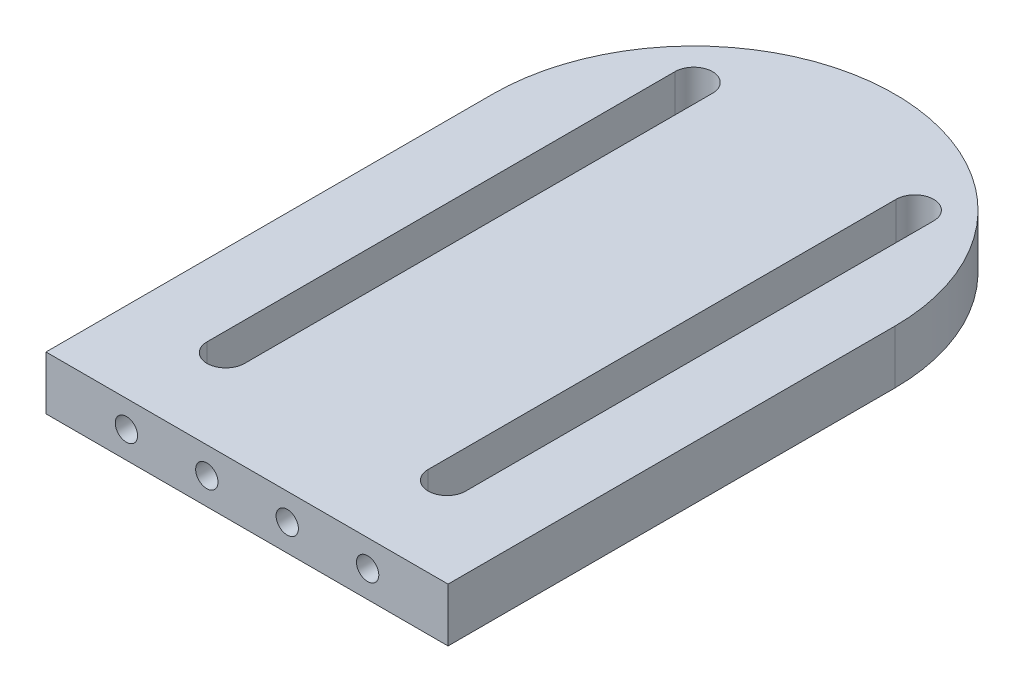
SolidWorks part; units mm, degrees
material "Сплав 2024"
ref_plane "Спереди" through (0, 0, 0) normal (0, 0, 1) x (1, 0, 0)
ref_plane "Сверху" through (0, 0, 0) normal (0, 1, 0) x (1, 0, 0)
ref_plane "Справа" through (0, 0, 0) normal (1, 0, 0) x (0, 0, -1)
sketch "Эскиз1" plane through (0, 0, 0) normal (0, 1, 0) x (1, 0, 0)
  line L2 (-15.9099, 15.9099) -> (15.9099, -15.9099) construction
  line L3 (15.9099, 15.9099) -> (-15.9099, -15.9099) construction
  line L4 (-22.5, 0) -> (-22.5, -50)
  line L5 (-22.5, -50) -> (22.5, -50)
  line L6 (22.5, 0) -> (22.5, -50)
  arc A0 (22.5, 0) -> (-22.5, 0) centre (0, 0) ccw
  dimension "D1" = 45
  dimension "D2" = 50
  dimension "D3" = 45
extrude "Бобышка-Вытянуть1" add sketch "Эскиз1" along normal blind 6
sketch "Эскиз2" plane through (0, 6, 0) normal (0, 1, 0) x (1, 0, 0)
  line L0 (-12.3744, -12.3744) -> (12.3744, 12.3744) construction
  line L1 (-36.6046, 36.6046) -> (36.6046, -36.6046) construction
  line L2 (22.5, -50) -> (22.5, 0) construction
  line L3 (-12.3744, 28.2466) -> (-12.3744, -50.5484) construction
  line L4 (12.3744, 23.4168) -> (12.3744, -56.6851) construction
  line L5 (-12.3744, 12.3744) -> (-12.3744, -40) construction
  line L6 (-10.2744, 12.3744) -> (-10.2744, -40)
  line L7 (-14.4744, 12.3744) -> (-14.4744, -40)
  line L8 (-22.5, -50) -> (22.5, -50) construction
  line L9 (0, 10.4779) -> (0, -10.8682) construction
  line L10 (12.3744, 12.3744) -> (12.3744, -40) construction
  line L11 (10.2744, 12.3744) -> (10.2744, -40)
  line L12 (14.4744, 12.3744) -> (14.4744, -40)
  circle A0 centre (0, 0) radius 6 construction
  circle A1 centre (0, 0) radius 17.5 construction
  arc A2 (-10.2744, 12.3744) -> (-14.4744, 12.3744) centre (-12.3744, 12.3744) ccw
  arc A3 (-14.4744, -40) -> (-10.2744, -40) centre (-12.3744, -40) ccw
  arc A4 (10.2744, 12.3744) -> (14.4744, 12.3744) centre (12.3744, 12.3744) cw
  arc A5 (14.4744, -40) -> (10.2744, -40) centre (12.3744, -40) cw
  point P12 (-12.3744, 12.3744)
  point P13 (12.3744, 12.3744)
  point P18 (-12.3744, -13.8128)
  point P28 (12.3744, -13.8128)
  dimension "D1" = 12
  dimension "D2" = 35
  dimension "D4" = 2.1
  dimension "D3" = 45
  dimension "D5" = 10
hole_wizard "Цековка для  винта с полукруглой головкой M31" [suppressed] positions "Эскиз4" profile "Эскиз5" counterbore size "M3" standard "Ansi Metric"
sketch "Эскиз4" plane through (0, 6, 0) normal (0, 1, 0) x (1, 0, 0)
  line L2 (-36.6046, 36.6046) -> (36.6046, -36.6046) construction
  line L3 (-12.3744, -12.3744) -> (12.3744, 12.3744) construction
  circle A0 centre (0, 0) radius 6 construction
  point P0 (-4.2426, 4.2426)
  point P6 (-4.2426, -4.2426)
  point P10 (4.2426, -4.2426)
  point P12 (4.2426, 4.2426)
sketch "Эскиз5" plane through (-4.2426, 6, -4.2426) normal (1, 0, 0) x (0, 0, 1)
  line L0 (0, 0) -> (0, 6)
  line L1 (0, 6) -> (1.7, 6)
  line L3 (1.7, 6) -> (1.7, 2)
  line L4 (1.7, 2) -> (3.35, 2)
  line L5 (3.35, 2) -> (3.35, 0)
  line L7 (3.35, 0) -> (0, 0)
  line L11 (0, -6.35) -> (0, 107.95) construction
  dimension "Диаметр сквозного отверстия" = 3.4
  dimension "Глубина сквозного отверстия" = 6
  dimension "Диаметр цековки" = 6.7
  dimension "Глубина цековки" = 2
hole_wizard "Отверстие обработанное метчиком M4x0.71" [suppressed] positions "Эскиз7" profile "Эскиз6" tap size "M4x0.7" standard "Ansi Metric"
sketch "Эскиз7" [suppressed] plane through (0, 4, 0) normal (0, 1, 0) x (1, 0, 0)
  line L0 (22.5, 0) -> (-22.5, 0) construction
  line L1 (0, 22.5) -> (0, -22.5) construction
  circle A0 centre (0, 0) radius 19.25 construction
  point P0 (-19.25, 0)
  point P6 (0, -19.25)
  point P10 (19.25, 0)
  point P12 (0, 19.25)
sketch "Эскиз6" plane through (-19.25, 4, 0) normal (1, 0, 0) x (0, 0, 1)
  line L0 (0, 0) -> (0, 4)
  line L1 (0, 4) -> (1.65, 4)
  line L2 (1.65, 4) -> (1.65, 0)
  line L5 (1.65, 0) -> (0, 0)
  line L11 (0, -6.35) -> (0, 107.95) construction
  dimension "Диаметр резьбы" = 3.3
  dimension "Глубина проходного сверла" = 4
extrude "Вырез-Вытянуть1" cut sketch "Эскиз2" against normal through all
sketch "Эскиз8" plane through (0, 0, 50) normal (0, 0, 1) x (1, 0, 0)
  line L0 (-22.5, 3) -> (22.5, 3) construction
  line L1 (-22.5, 6) -> (-22.5, 0) construction
  line L2 (22.5, 6) -> (22.5, 0) construction
  line L3 (-13.5, 6) -> (-13.5, 0) construction
  line L4 (-22.5, 6) -> (22.5, 6) construction
  line L5 (-22.5, 0) -> (22.5, 0) construction
  line L6 (-4.5, 6) -> (-4.5, 0) construction
  line L7 (4.5, 6) -> (4.5, 0) construction
  line L8 (13.5, 6) -> (13.5, 0) construction
  line L9 (-22.5, 0) -> (22.5, 0) construction
  dimension "D1" = 9
  dimension "D2" = 9
  dimension "D3" = 9
  dimension "D4" = 9
hole_wizard "Отверстие обработанное метчиком M3x0.51" positions "Эскиз10" profile "Эскиз9" tap size "M3x0.5" standard "Ansi Metric"
sketch "Эскиз10" plane through (0, 0, 50) normal (0, 0, 1) x (1, 0, 0)
  line L0 (-13.5, 6) -> (-13.5, 0) construction
  line L1 (-4.5, 6) -> (-4.5, 0) construction
  line L2 (4.5, 6) -> (4.5, 0) construction
  line L3 (13.5, 6) -> (13.5, 0) construction
  point P0 (-13.5, 3)
  point P4 (-4.5, 3)
  point P8 (4.5, 3)
  point P12 (13.5, 3)
sketch "Эскиз9" plane through (-13.5, 3, 50) normal (1, 0, 0) x (0, -1, 0)
  line L0 (0, 0) -> (0, 9.2511)
  line L1 (0, 9.2511) -> (1.25, 8.5)
  line L2 (1.25, 8.5) -> (1.25, 0)
  line L5 (1.25, 0) -> (0, 0)
  line L10 (0, 9.2511) -> (-1.25, 8.5) construction
  line L11 (0, -6.35) -> (0, 107.95) construction
  dimension "Диаметр сверла" = 2.5
  dimension "Глубина сверла" = 8.5
  dimension "Угол заточки сверла" = 118
cosmetic thread "Отверстие резьбы1" parameters "D1"=6, "D2"=3
cosmetic thread "Отверстие резьбы2" parameters "D1"=6, "D2"=3
cosmetic thread "Отверстие резьбы3" parameters "D1"=6, "D2"=3
cosmetic thread "Отверстие резьбы4" parameters "D1"=6, "D2"=3
equation "\"D1@Эскиз8\"=\"D1@Эскиз1\"/5"
equation "\"D2@Эскиз8\"=\"D1@Эскиз8\""
equation "\"D3@Эскиз8\"=\"D1@Эскиз8\""
equation "\"D4@Эскиз8\"=\"D1@Эскиз8\""
